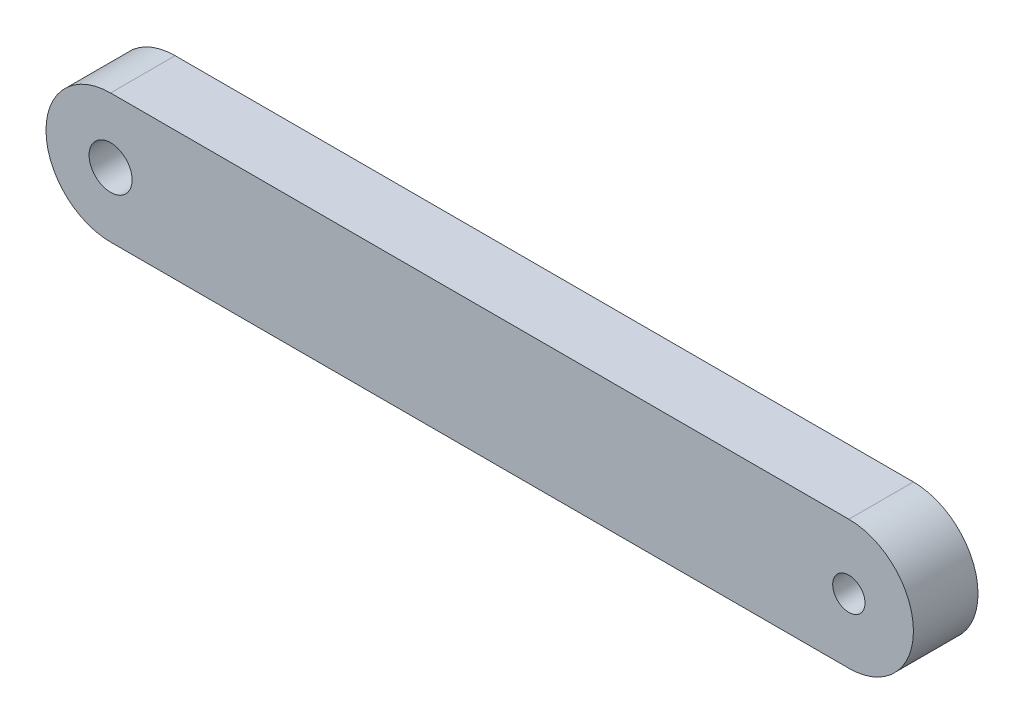
SolidWorks part; units mm, degrees
material "Plain Carbon Steel"
ref_plane "Front Plane" through (0, 0, 0) normal (0, 0, 1) x (1, 0, 0)
ref_plane "Top Plane" through (0, 0, 0) normal (0, 1, 0) x (1, 0, 0)
ref_plane "Right Plane" through (0, 0, 0) normal (1, 0, 0) x (0, 0, -1)
sketch "Sketch1" plane through (0, 0, 0) normal (0, 0, 1) x (1, 0, 0)
  line L0 (-16.1948, 0) -> (18.1052, 0) construction
  line L1 (-16.1948, 3) -> (18.1052, 3)
  line L2 (-16.1948, -3) -> (18.1052, -3)
  arc A0 (-16.1948, 3) -> (-16.1948, -3) centre (-16.1948, 0) ccw
  arc A1 (18.1052, -3) -> (18.1052, 3) centre (18.1052, 0) ccw
  point P3 (0.9552, 0)
  dimension "D1" = 34.3
  dimension "D2" = 6
extrude "Boss-Extrude1" add sketch "Sketch1" along normal blind 3
sketch "Sketch2" plane through (0, 0, 3) normal (0, 0, 1) x (1, 0, 0)
  circle A0 centre (18.1052, 0) radius 0.75
  circle A4 centre (-16.1948, 0) radius 1
  dimension "D1" = 2
  dimension "D2" = 1.5
extrude "Cut-Extrude1" cut sketch "Sketch2" against normal through all
